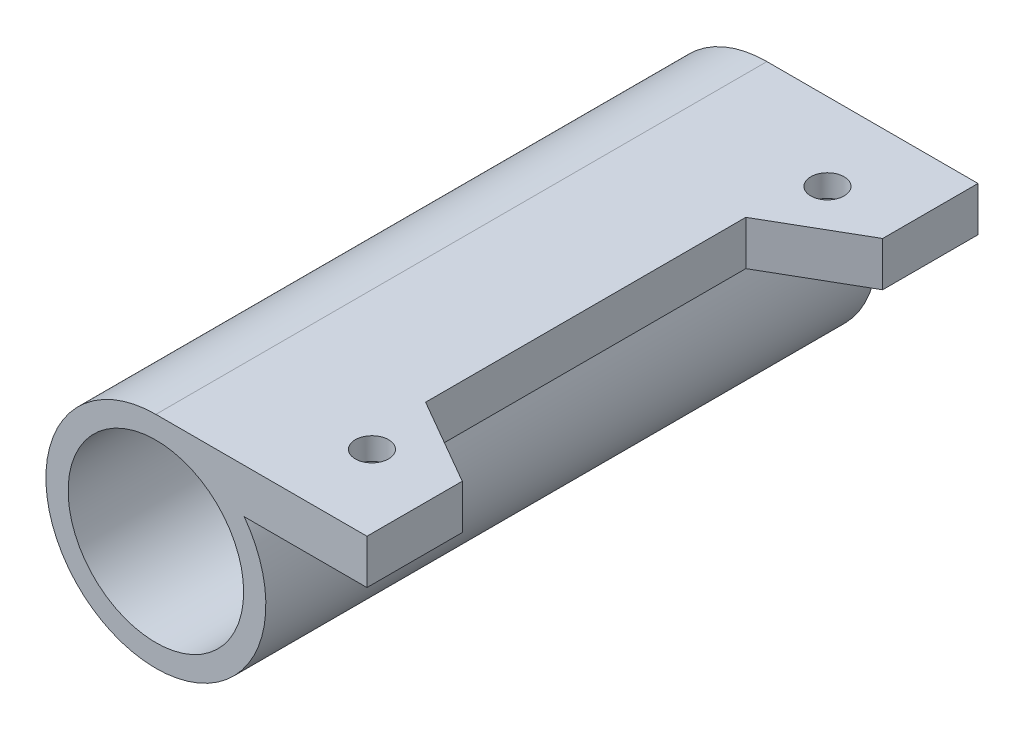
SolidWorks part; units mm, degrees
ref_plane "Спереди" through (0, 0, 0) normal (0, 0, 1) x (1, 0, 0)
ref_plane "Сверху" through (0, 0, 0) normal (0, 1, 0) x (1, 0, 0)
ref_plane "Справа" through (0, 0, 0) normal (1, 0, 0) x (0, 0, -1)
sketch "Эскиз2" plane through (0, 0, 0) normal (0, 0, 1) x (1, 0, 0)
  line L0 (0, 9.9) -> (19, 9.9)
  line L1 (19, 9.9) -> (19, 5.9)
  line L2 (19, 5.9) -> (7.9498, 5.9)
  circle A0 centre (0, 0) radius 7.9
  circle A1 centre (0, 0) radius 9.9
  dimension "D2" = 15.8
  dimension "D3" = 19.8
  dimension "D1" = 4
  dimension "D4" = 19
extrude "Бобышка-Вытянуть1" add sketch "Эскиз2" against normal blind 7 and the other way blind 48 contours A1 A0 | A1 L2 L1 L0
sketch "Эскиз3" plane through (0, 5.9, 0) normal (0, -1, 0) x (1, 0, 0)
  line L0 (19, -7) -> (7.9498, -7) construction
  line L1 (15.4498, -1.7321) -> (15.4498, 1.7321)
  line L2 (15.4498, 1.7321) -> (12.4498, 3.4641)
  line L3 (12.4498, 3.4641) -> (9.4498, 1.7321)
  line L4 (9.4498, 1.7321) -> (9.4498, -1.7321)
  line L5 (9.4498, -1.7321) -> (12.4498, -3.4641)
  line L6 (12.4498, -3.4641) -> (15.4498, -1.7321)
  line L7 (19, 20.5) -> (-7.1059, 20.5) construction
  line L8 (19, 48) -> (19, -7) construction
  line L9 (12.4498, 44.4641) -> (15.4498, 42.7321)
  line L10 (9.4498, 42.7321) -> (12.4498, 44.4641)
  line L11 (9.4498, 39.2679) -> (9.4498, 42.7321)
  line L12 (12.4498, 37.5359) -> (9.4498, 39.2679)
  line L13 (15.4498, 39.2679) -> (12.4498, 37.5359)
  line L14 (15.4498, 42.7321) -> (15.4498, 39.2679)
  circle A0 centre (12.4498, 0) radius 3 construction
  circle A1 centre (12.4498, 41) radius 3 construction
  dimension "D1" = 6
  dimension "D2" = 4.5
  dimension "D3" = 7
extrude "Вырез-Вытянуть1" cut sketch "Эскиз3" against normal blind 2
sketch "Эскиз4" plane through (0, 9.9, 0) normal (0, 1, 0) x (1, 0, 0)
  line L0 (19, -20.5) -> (0, -20.5) construction
  line L1 (19, -48) -> (19, 7) construction
  circle A0 centre (12.4498, 0) radius 1.5
  circle A1 centre (12.4498, -41) radius 1.5
  dimension "D1" = 3
extrude "Вырез-Вытянуть2" cut sketch "Эскиз4" against normal blind 10
sketch "Эскиз5" plane through (0, 9.9, 0) normal (0, 1, 0) x (1, 0, 0)
  line L0 (19, -1.5789) -> (11.1908, -6.0875)
  line L1 (19, -48) -> (19, 7) construction
  line L2 (11.1908, -6.0875) -> (11.1908, -34.9125)
  line L3 (11.1908, -34.9125) -> (19, -39.4211)
  line L4 (19, -39.4211) -> (19, -1.5789)
  line L5 (0, -48) -> (0, 7) construction
  point P4 (11.1908, -20.5)
  point P9 (0, -20.5)
  dimension "D1" = 120
  dimension "D2" = 120
extrude "Вырез-Вытянуть3" cut sketch "Эскиз5" against normal blind 10
